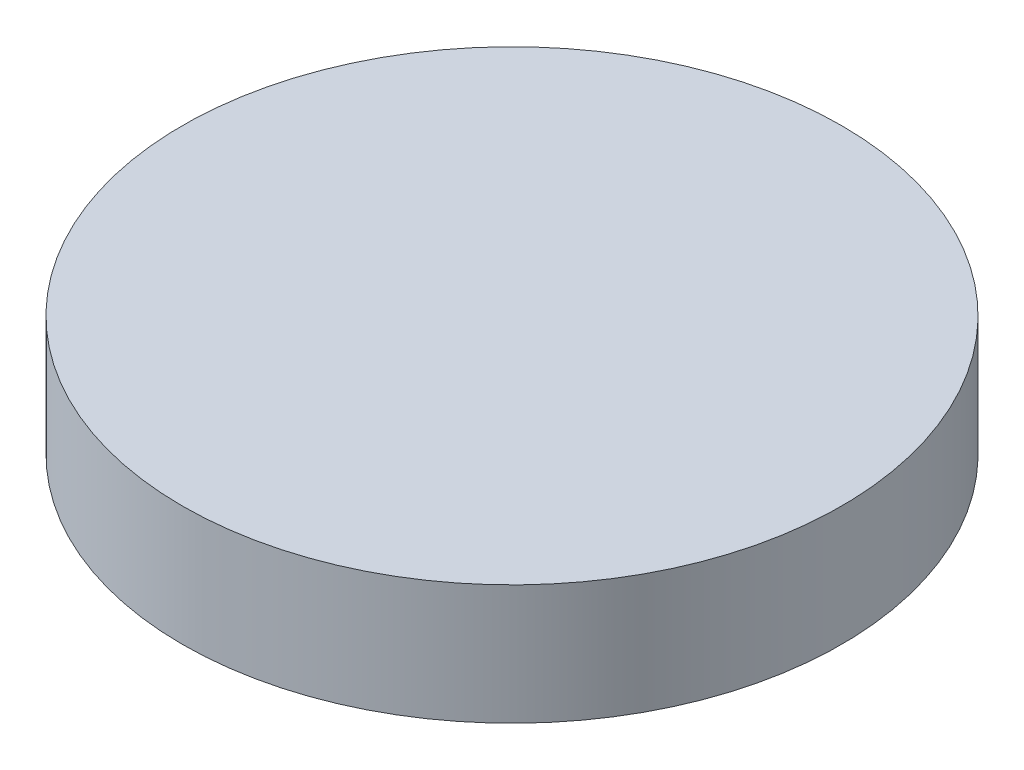
SolidWorks part; units mm, degrees
ref_plane "前视基准面" through (0, 0, 0) normal (0, 0, 1) x (1, 0, 0)
ref_plane "上视基准面" through (0, 0, 0) normal (0, 1, 0) x (1, 0, 0)
ref_plane "右视基准面" through (0, 0, 0) normal (1, 0, 0) x (0, 0, -1)
other "Configuration Table"
sketch "草图1" plane through (0, 0, 0) normal (0, 1, 0) x (1, 0, 0)
  circle A0 centre (0, 0) radius 27.5
  dimension "D1" = 55
extrude "凸台-拉伸1" add sketch "草图1" along normal blind 10
